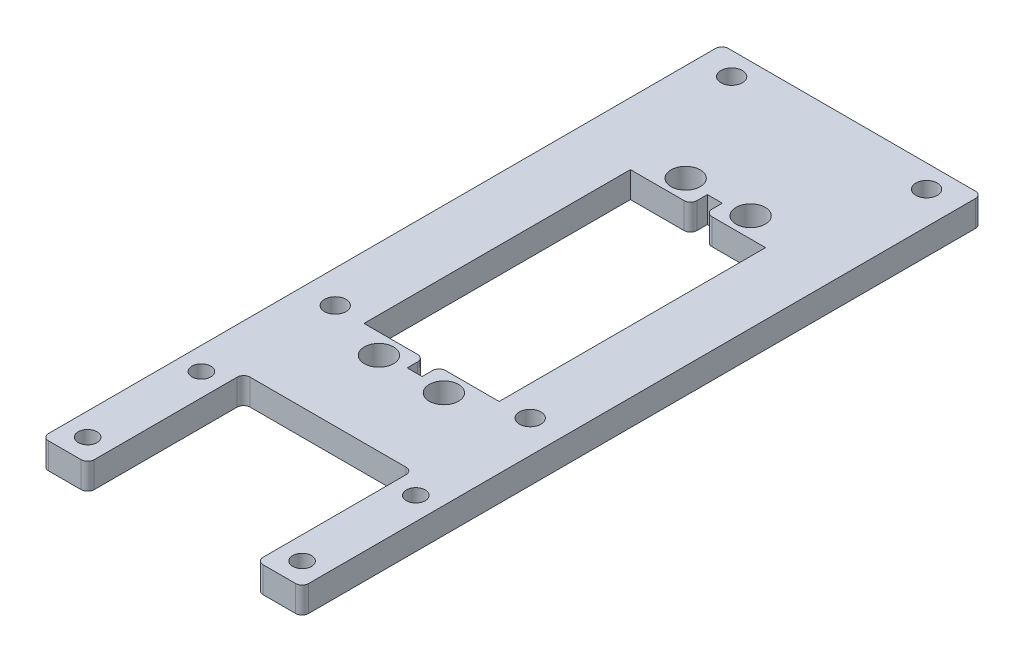
SolidWorks part; units mm, degrees
ref_plane "Front Plane" through (0, 0, 0) normal (0, 0, 1) x (1, 0, 0)
ref_plane "Top Plane" through (0, 0, 0) normal (0, 1, 0) x (1, 0, 0)
ref_plane "Right Plane" through (0, 0, 0) normal (1, 0, 0) x (0, 0, -1)
sketch "Sketch1" plane through (0, 0, 0) normal (0, 1, 0) x (1, 0, 0)
  line L1 (-20, -52.3) -> (20, -52.3)
  line L2 (-20, -52.3) -> (-20, 52.3)
  line L3 (-20, 52.3) -> (20, 52.3)
  line L4 (20, -52.3) -> (20, 52.3)
  line L5 (-20, -52.3) -> (20, 52.3) construction
  line L6 (-20, 52.3) -> (20, -52.3) construction
  point P0 (0, 0)
  dimension "D1" = 104.6
  dimension "D2" = 40
extrude "Boss-Extrude1" add sketch "Sketch1" along normal blind 4
sketch "Sketch2" plane through (0, 4, 0) normal (0, 1, 0) x (1, 0, 0)
  line L0 (0, 52.3) -> (0, -52.3) construction
  line L1 (20, 52.3) -> (-20, 52.3) construction
  line L2 (-20, -52.3) -> (20, -52.3) construction
  line L3 (-15, 48.8) -> (15, 48.8) construction
  line L4 (-15, -12.2) -> (15, -12.2) construction
  circle A0 centre (-15, 48.8) radius 1.65
  circle A1 centre (15, 48.8) radius 1.65
  circle A2 centre (-15, -12.2) radius 1.65
  circle A3 centre (15, -12.2) radius 1.65
  point P9 (0, 48.8)
  point P12 (0, -12.2)
  dimension "D1" = 3.3
  dimension "D2" = 30
  dimension "D3" = 61
  dimension "D4" = 3.5
extrude "Cut-Extrude1" cut sketch "Sketch2" against normal through all
sketch "Sketch3" plane through (0, 4, 0) normal (0, 1, 0) x (1, 0, 0)
  line L0 (0, 52.3) -> (0, -52.3) construction
  line L1 (20, 52.3) -> (-20, 52.3) construction
  line L2 (-20, -52.3) -> (20, -52.3) construction
  line L3 (-1.15, 31.2196) -> (-1.15, 28.6196)
  line L4 (-10.4, 28.6196) -> (-1.15, 28.6196)
  line L5 (-10.4, 28.6196) -> (-10.4, -12.3804)
  line L6 (-10.4, -12.3804) -> (-1.15, -12.3804)
  line L7 (10.4, 28.6196) -> (10.4, -12.3804)
  line L8 (-10.4, 28.6196) -> (10.4, -12.3804) construction
  line L9 (-10.4, -12.3804) -> (10.4, 28.6196) construction
  line L10 (-5, -15.4804) -> (5, -15.4804) construction
  line L11 (-5, -15.4804) -> (-5, 31.7196) construction
  line L12 (-5, 31.7196) -> (5, 31.7196) construction
  line L13 (5, -15.4804) -> (5, 31.7196) construction
  line L14 (-5, -15.4804) -> (5, 31.7196) construction
  line L15 (-5, 31.7196) -> (5, -15.4804) construction
  line L16 (-1.15, -14.9804) -> (1.15, -14.9804)
  line L17 (-1.15, -14.9804) -> (-1.15, 31.2196) construction
  line L18 (-1.15, 31.2196) -> (1.15, 31.2196)
  line L19 (1.15, -14.9804) -> (1.15, 31.2196) construction
  line L20 (-1.15, -14.9804) -> (1.15, 31.2196) construction
  line L21 (-1.15, 31.2196) -> (1.15, -14.9804) construction
  line L22 (1.15, 31.2196) -> (1.15, 28.6196)
  line L23 (-1.15, -12.3804) -> (-1.15, -14.9804)
  line L24 (1.15, -14.9804) -> (1.15, -12.3804)
  line L25 (1.15, 28.6196) -> (10.4, 28.6196)
  line L26 (1.15, -12.3804) -> (10.4, -12.3804)
  circle A0 centre (-5, 31.7196) radius 2.25
  circle A1 centre (5, 31.7196) radius 2.25
  circle A2 centre (-5, -15.4804) radius 2.25
  circle A3 centre (5, -15.4804) radius 2.25
  point P6 (0, 8.1196)
  point P11 (0, 8.1196)
  point P20 (0, 8.1196)
  dimension "D4" = 4.5
  dimension "D1" = 20.8
  dimension "D2" = 41
  dimension "D3" = 47.2
  dimension "D5" = 10
  dimension "D6" = 23.6804
  dimension "D7" = 2.3
  dimension "D8" = 2.6
extrude "Cut-Extrude2" cut sketch "Sketch3" against normal through all
sketch "Sketch4" plane through (0, 4, 0) normal (0, 1, 0) x (1, 0, 0)
  line L0 (0, 52.3) -> (0, -52.3) construction
  line L1 (20, 52.3) -> (-20, 52.3) construction
  line L2 (-20, -52.3) -> (20, -52.3) construction
  line L3 (-20, -40.05) -> (-13, -40.05) construction
  line L4 (-16.5, -48.8) -> (16.5, -48.8) construction
  line L5 (-16.5, -48.8) -> (-16.5, -31.3) construction
  line L6 (-16.5, -31.3) -> (16.5, -31.3) construction
  line L7 (16.5, -48.8) -> (16.5, -31.3) construction
  line L8 (-16.5, -48.8) -> (16.5, -31.3) construction
  line L9 (-16.5, -31.3) -> (16.5, -48.8) construction
  line L10 (-13, -52.3) -> (13, -52.3)
  line L11 (-13, -52.3) -> (-13, -28.3)
  line L12 (-13, -28.3) -> (13, -28.3)
  line L13 (13, -52.3) -> (13, -28.3)
  line L14 (-20, 52.3) -> (-20, -52.3) construction
  circle A0 centre (-16.5, -31.3) radius 1.45
  circle A1 centre (-16.5, -48.8) radius 1.45
  circle A2 centre (16.5, -31.3) radius 1.45
  circle A3 centre (16.5, -48.8) radius 1.45
  point P6 (0, -40.05)
  point P19 (0, -28.3)
  point P24 (-16.5, -40.05)
  dimension "D3" = 2.9
  dimension "D1" = 33
  dimension "D2" = 17.5
  dimension "D4" = 3.5
  dimension "D5" = 24
extrude "Cut-Extrude3" cut sketch "Sketch4" against normal through all
fillet "Fillet1" radius 1 12 edges at (1.15, 2, 12.3804) (-1.15, 2, 12.3804) (1.15, 2, -28.6196) (-1.15, 2, -28.6196) (-20, 2, -52.3) (20, 2, -52.3) (-13, 2, 28.3) (13, 2, 28.3) (20, 2, 52.3) (13, 2, 52.3) (-13, 2, 52.3) (-20, 2, 52.3)
